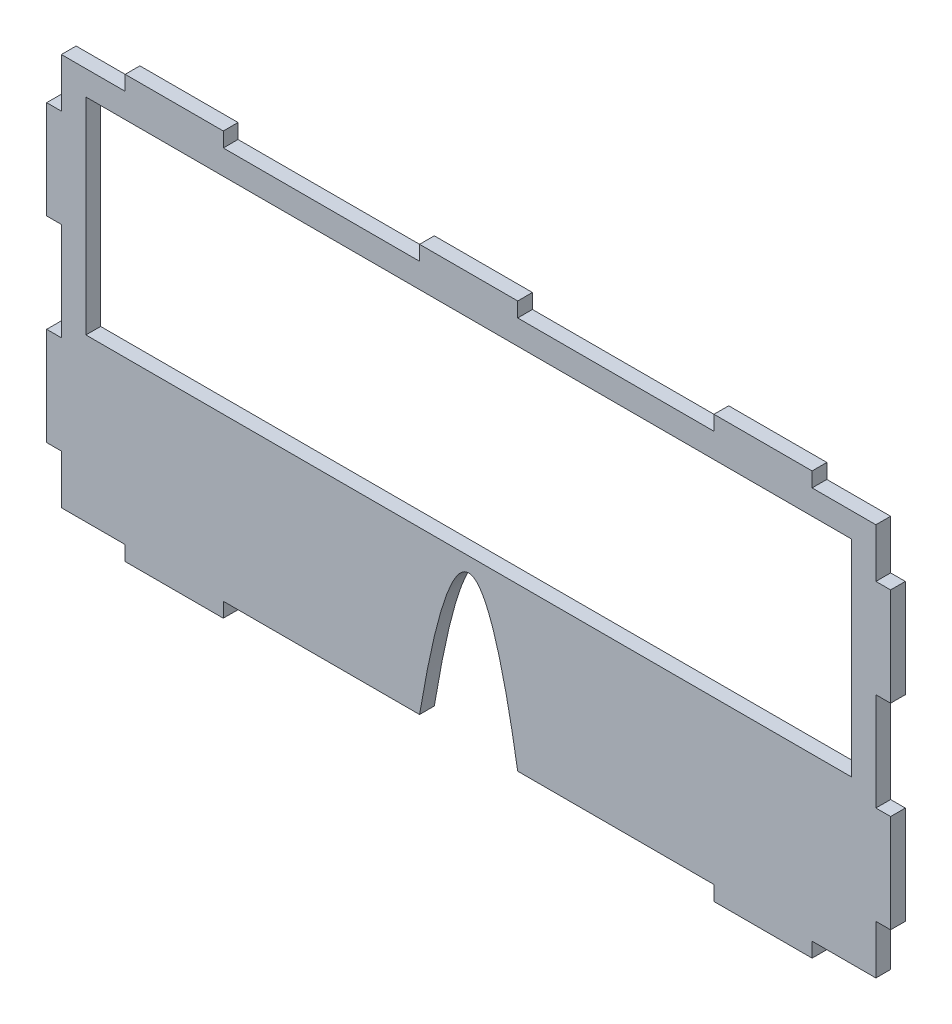
SolidWorks part; units mm, degrees
ref_plane "Plan de face" through (0, 0, 0) normal (0, 0, 1) x (1, 0, 0)
ref_plane "Plan de dessus" through (0, 0, 0) normal (0, 1, 0) x (1, 0, 0)
ref_plane "Plan de droite" through (0, 0, 0) normal (1, 0, 0) x (0, 0, -1)
sketch "Esquisse1" plane through (0, 0, 0) normal (0, 0, 1) x (1, 0, 0)
  line L0 (0, 0) -> (0, 10)
  line L5 (0, 10) -> (3, 10)
  line L6 (3, 10) -> (3, 30)
  line L7 (0, 30) -> (3, 30)
  line L8 (0, 30) -> (0, 50)
  line L9 (0, 50) -> (3, 50)
  line L10 (3, 50) -> (3, 70)
  line L11 (3, 70) -> (0, 70)
  line L12 (0, 70) -> (0, 80)
  line L13 (0, 80) -> (-13, 80)
  line L14 (-13, 80) -> (-13, 83)
  line L15 (-13, 83) -> (-33, 83)
  line L16 (-33, 83) -> (-33, 80)
  line L17 (-33, 80) -> (-73, 80)
  line L18 (-73, 80) -> (-73, 83)
  line L19 (-73, 83) -> (-93, 83)
  line L20 (-93, 83) -> (-93, 80)
  line L21 (-93, 80) -> (-133, 80)
  line L22 (-133, 80) -> (-133, 83)
  line L23 (-133, 83) -> (-153, 83)
  line L24 (-153, 83) -> (-153, 80)
  line L25 (-153, 80) -> (-166, 80)
  line L26 (-166, 80) -> (-166, 70)
  line L27 (-166, 70) -> (-169, 70)
  line L28 (-169, 70) -> (-169, 50)
  line L29 (-169, 50) -> (-166, 50)
  line L30 (-166, 50) -> (-166, 30)
  line L31 (-166, 30) -> (-169, 30)
  line L32 (-169, 30) -> (-169, 10)
  line L33 (-169, 10) -> (-166, 10)
  line L34 (-166, 10) -> (-166, 0)
  line L35 (-166, 0) -> (-153, 0)
  line L36 (-153, 0) -> (-153, -3)
  line L37 (-153, -3) -> (-133, -3)
  line L38 (0, 0) -> (-13, 0)
  line L39 (-13, 0) -> (-13, -3)
  line L40 (-13, -3) -> (-33, -3)
  line L41 (-33, -3) -> (-33, 0)
  line L42 (-33, 0) -> (-73, 0)
  line L43 (-133, -3) -> (-133, 0)
  line L44 (-133, 0) -> (-93, 0)
  line L45 (-93, 0) -> (-73, 0) construction
  line L47 (-161, 75) -> (-5, 75)
  line L48 (-161, 75) -> (-161, 33)
  line L49 (-161, 33) -> (-5, 33)
  line L50 (-5, 75) -> (-5, 33)
  spline S0 degree 2 poles (-93, 0) (-83, 60) (-73, 0) knots 0 0 0 1 1 1
  point P2 (-153, -1.5)
  dimension "D40" = 33
  dimension "D1" = 10
  dimension "D2" = 3
  dimension "D3" = 20
  dimension "D4" = 3
  dimension "D5" = 20
  dimension "D6" = 3
  dimension "D7" = 20
  dimension "D8" = 10
  dimension "D9" = 13
  dimension "D10" = 20
  dimension "D11" = 3
  dimension "D12" = 40
  dimension "D13" = 3
  dimension "D14" = 3
  dimension "D15" = 20
  dimension "D16" = 3
  dimension "D17" = 40
  dimension "D18" = 3
  dimension "D19" = 20
  dimension "D20" = 3
  dimension "D21" = 13
  dimension "D22" = 10
  dimension "D23" = 3
  dimension "D24" = 20
  dimension "D25" = 3
  dimension "D26" = 20
  dimension "D27" = 3
  dimension "D28" = 20
  dimension "D29" = 3
  dimension "D30" = 3
  dimension "D31" = 13
  dimension "D32" = 20
  dimension "D33" = 3
  dimension "D34" = 20
  dimension "D35" = 13
  dimension "D36" = 5
  dimension "D37" = 5
  dimension "D38" = 5
  dimension "D39" = 3
  dimension "D41" = 40
  dimension "D42" = 40
extrude "Boss.-Extru.1" add sketch "Esquisse1" along normal blind 3
